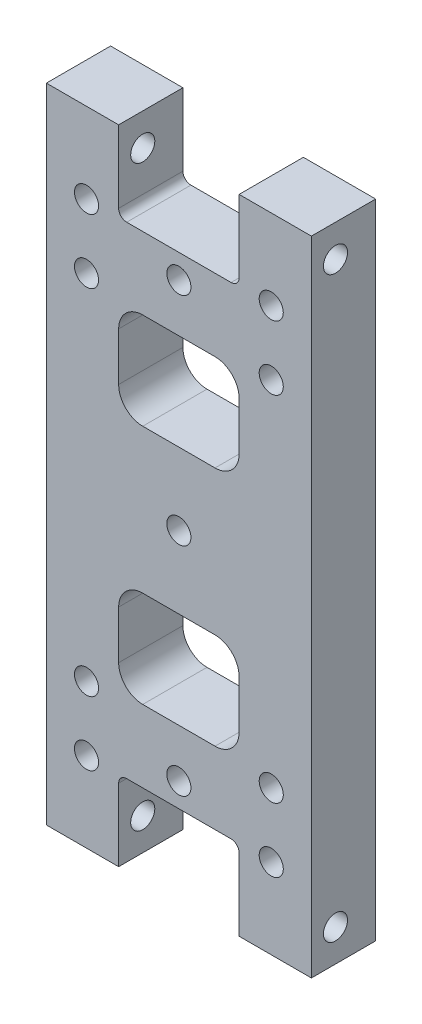
SolidWorks part; units mm, degrees
material "POM 乙缩醛共聚物"
ref_plane "前视基准面" through (0, 0, 0) normal (0, 0, 1) x (1, 0, 0)
ref_plane "上视基准面" through (0, 0, 0) normal (0, 1, 0) x (1, 0, 0)
ref_plane "右视基准面" through (0, 0, 0) normal (1, 0, 0) x (0, 0, -1)
sketch "草图1" plane through (0, 0, 0) normal (0, 0, 1) x (1, 0, 0)
  line L0 (-16.5, -40) -> (16.5, -40)
  line L1 (-16.5, -40) -> (-16.5, 40)
  line L2 (-16.5, 40) -> (16.5, 40)
  line L3 (16.5, -40) -> (16.5, 40)
  line L4 (-16.5, -40) -> (16.5, 40) construction
  line L5 (-16.5, 40) -> (16.5, -40) construction
  point P0 (0, 0)
  dimension "D1" = 33
  dimension "D2" = 80
extrude "凸台-拉伸1" add sketch "草图1" along normal blind 8
sketch "草图2" plane through (0, 0, 8) normal (0, 0, 1) x (1, 0, 0)
  line L0 (0, 40) -> (0, -40) construction
  line L1 (16.5, 40) -> (-16.5, 40) construction
  line L2 (-16.5, -40) -> (16.5, -40) construction
  line L3 (-16.5, 0) -> (16.5, 0) construction
  line L4 (-16.5, 40) -> (-16.5, -40) construction
  line L5 (16.5, -40) -> (16.5, 40) construction
  line L18 (-7.5, -40) -> (7.5, -30) construction
  line L19 (-7.5, 30) -> (7.5, 30)
  line L20 (-7.5, 30) -> (-7.5, 40)
  line L21 (-7.5, 40) -> (7.5, 40)
  line L22 (7.5, 30) -> (7.5, 40)
  line L23 (-7.5, 30) -> (7.5, 40) construction
  line L24 (-7.5, 40) -> (7.5, 30) construction
  line L25 (-7.5, -30) -> (7.5, -40) construction
  line L26 (7.5, -30) -> (7.5, -40)
  line L27 (-7.5, -40) -> (7.5, -40)
  line L28 (-7.5, -30) -> (-7.5, -40)
  line L29 (-7.5, -30) -> (7.5, -30)
  point P22 (0, 35)
  point P31 (0, -35)
  dimension "D1" = 7.5
  dimension "D4" = 10
extrude "切除-拉伸1" cut sketch "草图2" against normal through all
sketch "草图3" plane through (0, 0, 8) normal (0, 0, 1) x (1, 0, 0)
  line L0 (0, 30) -> (0, -30) construction
  line L1 (-7.5, 30) -> (7.5, 30) construction
  line L2 (7.5, -30) -> (-7.5, -30) construction
  line L3 (-16.5, 0) -> (16.5, 0) construction
  line L4 (-16.5, 40) -> (-16.5, -40) construction
  line L5 (16.5, -40) -> (16.5, 40) construction
  line L6 (11.5, 40) -> (11.5, -40) construction
  line L7 (16.5, 40) -> (7.5, 40) construction
  line L8 (7.5, -40) -> (16.5, -40) construction
  circle A1 centre (11.5, 22) radius 1.5
  circle A2 centre (11.5, 30) radius 1.5
  circle A5 centre (11.5, -30) radius 1.5
  circle A6 centre (11.5, -22) radius 1.5
  circle A7 centre (-11.5, -22) radius 1.5
  circle A8 centre (-11.5, -30) radius 1.5
  circle A11 centre (-11.5, 30) radius 1.5
  circle A12 centre (-11.5, 22) radius 1.5
  dimension "D2" = 3
  dimension "D1" = 22
  dimension "D3" = 11.5
  dimension "D4" = 8
extrude "切除-拉伸2" cut sketch "草图3" against normal through all
sketch "草图4" plane through (-16.5, 0, 0) normal (-1, 0, 0) x (0, 0, 1)
  line L0 (5, 30) -> (5, -30) construction
  line L1 (8, 40) -> (0, 40) construction
  line L3 (0, 0) -> (8, 0) construction
  line L4 (8, 40) -> (8, -40) construction
  circle A0 centre (5, 36) radius 1.5
  circle A1 centre (5, -36) radius 1.5
  dimension "D1" = 3
  dimension "D2" = 4
  dimension "D3" = 3
extrude "切除-拉伸3" cut sketch "草图4" against normal through all
fillet "圆角2" radius 1 4 edges at (-7.5, 30, 4) (7.5, 30, 4) (7.5, -30, 4) (-7.5, -30, 4)
sketch "草图5" plane through (0, 0, 0) normal (0, 0, -1) x (-1, 0, 0)
  line L0 (0, 30) -> (0, -30) construction
  line L1 (6.5, 30) -> (-6.5, 30) construction
  line L2 (-6.5, -30) -> (6.5, -30) construction
  line L3 (-16.5, 0) -> (16.5, 0) construction
  line L4 (-16.5, -40) -> (-16.5, 40) construction
  line L5 (16.5, 40) -> (16.5, -40) construction
  circle A0 centre (0, 0) radius 1.5
  circle A1 centre (0, 27) radius 1.5
  circle A2 centre (0, -27) radius 1.5
  dimension "D1" = 3
  dimension "D2" = 3
extrude "切除-拉伸4" cut sketch "草图5" against normal through all
sketch "草图7" plane through (0, 0, 0) normal (0, 0, -1) x (-1, 0, 0)
  line L0 (0, 30) -> (0, -30) construction
  line L1 (6.5, 30) -> (-6.5, 30) construction
  line L2 (-6.5, -30) -> (6.5, -30) construction
  line L3 (16.5, 0) -> (-16.5, 0) construction
  line L4 (-7.5, 21) -> (7.5, 21)
  line L5 (-7.5, 21) -> (-7.5, 9)
  line L6 (-7.5, 9) -> (7.5, 9)
  line L7 (7.5, 21) -> (7.5, 9)
  line L8 (-7.5, 21) -> (7.5, 9) construction
  line L9 (-7.5, 9) -> (7.5, 21) construction
  line L10 (16.5, 40) -> (16.5, -40) construction
  line L11 (-16.5, -40) -> (-16.5, 40) construction
  line L12 (-7.5, -9) -> (7.5, -21) construction
  line L13 (-7.5, -21) -> (7.5, -9) construction
  line L14 (7.5, -21) -> (7.5, -9)
  line L15 (-7.5, -9) -> (7.5, -9)
  line L16 (-7.5, -21) -> (-7.5, -9)
  line L17 (-7.5, -21) -> (7.5, -21)
  point P6 (0, 15)
  point P21 (0, -15)
  dimension "D1" = 12
  dimension "D2" = 15
  dimension "D3" = 15
extrude "切除-拉伸5" cut sketch "草图7" against normal through all
fillet "圆角3" radius 3 8 edges at (7.5, -21, 4) (-7.5, -21, 4) (-7.5, -9, 4) (7.5, -9, 4) (7.5, 9, 4) (-7.5, 9, 4) (-7.5, 21, 4) (7.5, 21, 4)
sketch "草图8" plane through (0, 0, 0) normal (0, 0, -1) x (-1, 0, 0)
  circle A0 centre (11.5, 30) radius 3
  circle A1 centre (-11.5, 30) radius 3
  circle A2 centre (-11.5, -30) radius 3
  circle A3 centre (11.5, -30) radius 3
  circle A4 centre (0, 0) radius 3
  dimension "D1" = 6
  dimension "D2" = 6
extrude "切除-拉伸6" cut sketch "草图8" against normal blind 3.5
